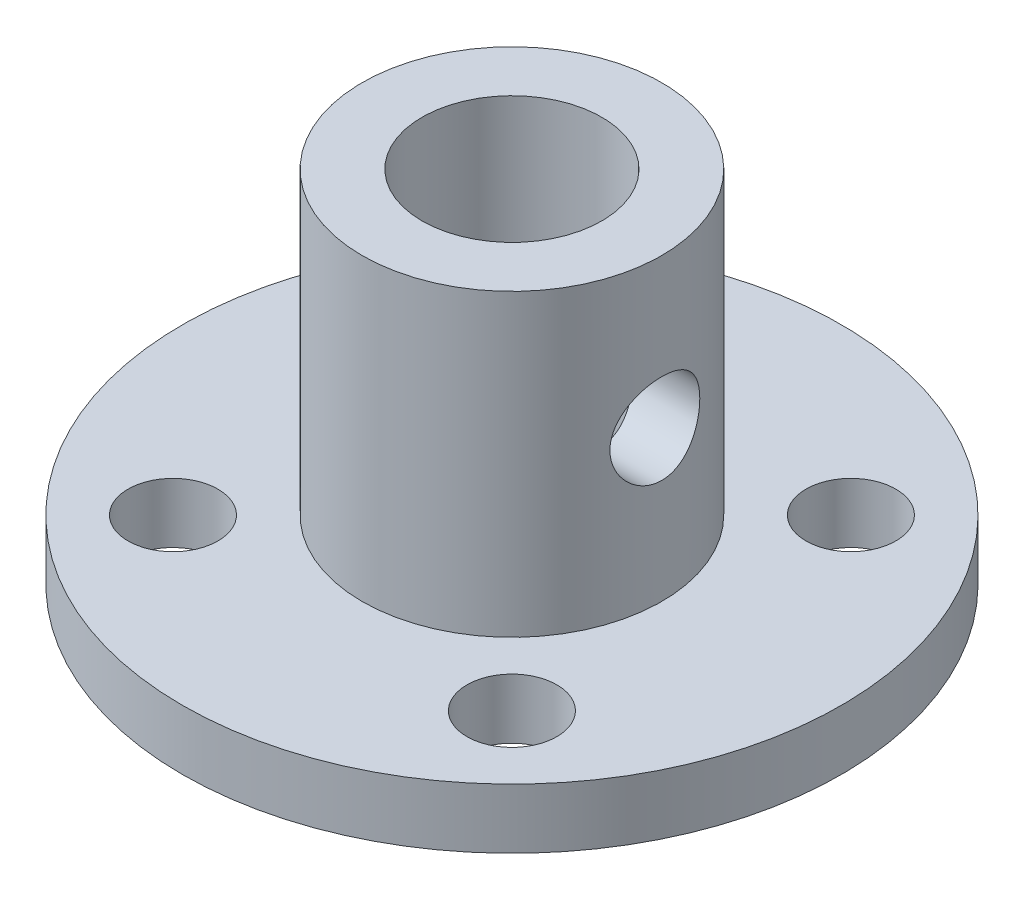
SolidWorks part; units mm, degrees
ref_plane "Front Plane" through (0, 0, 0) normal (0, 0, 1) x (1, 0, 0)
ref_plane "Top Plane" through (0, 0, 0) normal (0, 1, 0) x (1, 0, 0)
ref_plane "Right Plane" through (0, 0, 0) normal (1, 0, 0) x (0, 0, -1)
sketch "Sketch1" plane through (0, 0, 0) normal (0, 1, 0) x (1, 0, 0)
  circle A0 centre (0, 0) radius 11
  dimension "D1" = 22
extrude "Boss-Extrude1" add sketch "Sketch1" along normal blind 2
sketch "Sketch2" plane through (0, 2, 0) normal (0, 1, 0) x (1, 0, 0)
  circle A0 centre (0, 0) radius 5
  dimension "D1" = 10
extrude "Boss-Extrude2" add sketch "Sketch2" along normal blind 10
sketch "Sketch3" plane through (0, 12, 0) normal (0, 1, 0) x (1, 0, 0)
  circle A0 centre (0, 0) radius 3
  dimension "D1" = 6
extrude "Cut-Extrude1" cut sketch "Sketch3" against normal through all
sketch "Sketch4" plane through (0, 2, 0) normal (0, 1, 0) x (1, 0, 0)
  line L0 (0, 0) -> (0, 8) construction
  line L1 (0, 0) -> (5.6569, 5.6569) construction
  circle A1 centre (5.6569, 5.6569) radius 1.5
  dimension "D1" = 45
  dimension "D3" = 3
  dimension "D2" = 8
extrude "Cut-Extrude2" cut sketch "Sketch4" against normal through all
pattern_circular "CirPattern1" count 4 over 360 about axis through (0, 0, 0) along (0, 1, 0) of "Cut-Extrude2"
ref_plane "Plane1" through (11, 0, 0) normal (1, 0, 0) x (0, 0, -1)
sketch "Sketch5" plane through (11, 0, 0) normal (1, 0, 0) x (0, 0, -1)
  line L0 (3, 12) -> (-3, 12) construction
  circle A0 centre (0, 7) radius 1.5
  dimension "D1" = 3
  dimension "D2" = 5
extrude "Cut-Extrude3" cut sketch "Sketch5" against normal through all
